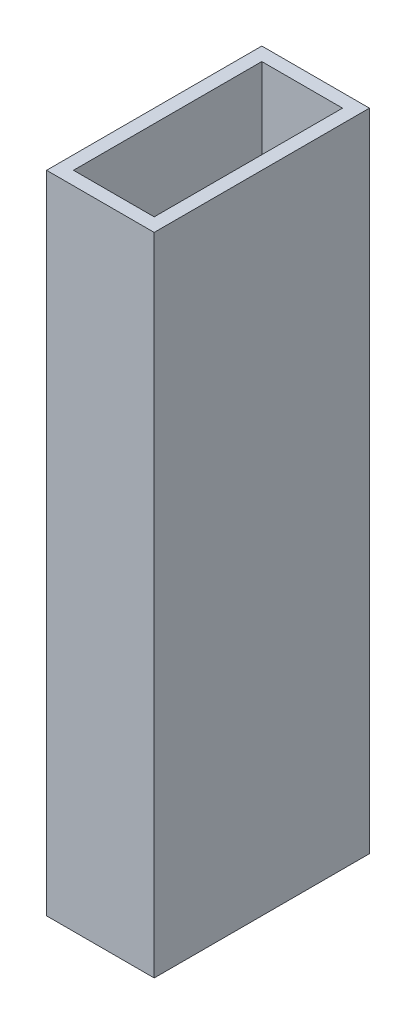
SolidWorks part; units mm, degrees
ref_plane "Front Plane" through (0, 0, 0) normal (0, 0, 1) x (1, 0, 0)
ref_plane "Top Plane" through (0, 0, 0) normal (0, 1, 0) x (1, 0, 0)
ref_plane "Right Plane" through (0, 0, 0) normal (1, 0, 0) x (0, 0, -1)
sketch "Sketch1" plane through (0, 0, 0) normal (0, 1, 0) x (1, 0, 0)
  line L0 (-9.525, -22.225) -> (-9.525, 22.225)
  line L1 (-12.7, -25.4) -> (12.7, -25.4)
  line L2 (-12.7, -25.4) -> (-12.7, 25.4)
  line L3 (-12.7, 25.4) -> (12.7, 25.4)
  line L4 (12.7, -25.4) -> (12.7, 25.4)
  line L5 (-12.7, -25.4) -> (12.7, 25.4) construction
  line L6 (-12.7, 25.4) -> (12.7, -25.4) construction
  line L7 (-9.525, 22.225) -> (9.525, 22.225)
  line L8 (9.525, -22.225) -> (9.525, 22.225)
  line L9 (-9.525, -22.225) -> (9.525, -22.225)
  point P0 (0, 0)
  dimension "D1" = 25.4
  dimension "D2" = 50.8
  dimension "D3" = 3.175
extrude "Boss-Extrude1" add sketch "Sketch1" along normal blind 152.4
